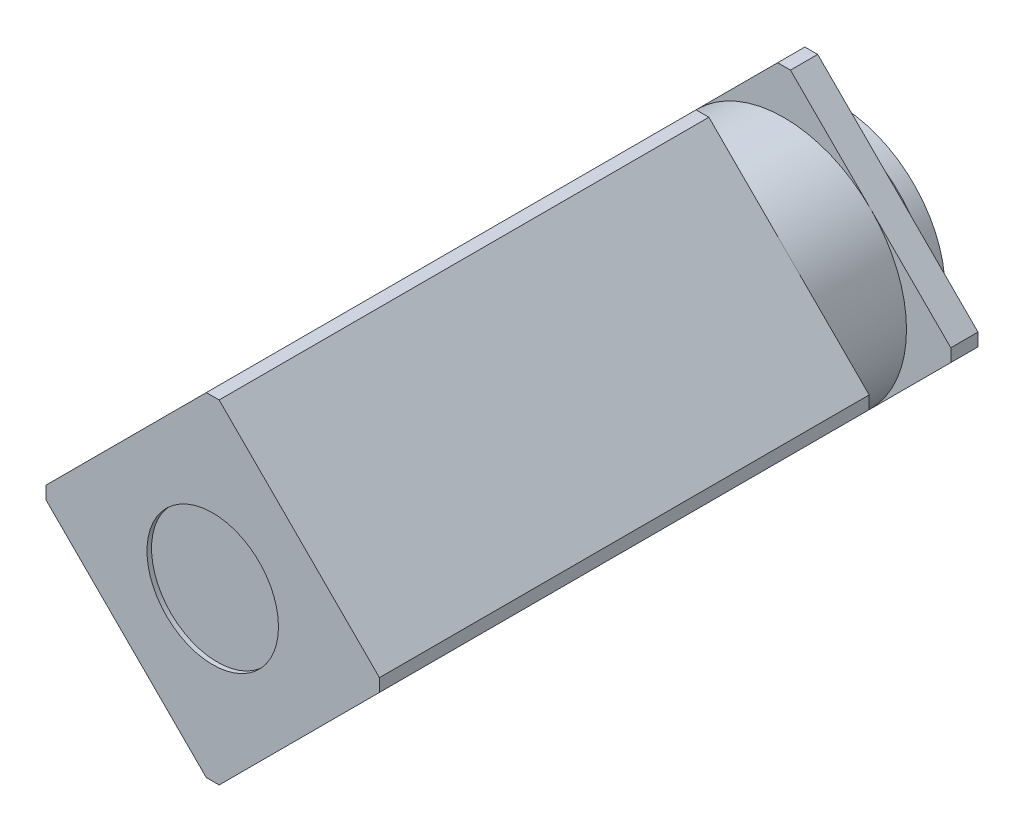
SolidWorks part; units mm, degrees
ref_plane "정면" through (0, 0, 0) normal (0, 0, 1) x (1, 0, 0)
ref_plane "윗면" through (0, 0, 0) normal (0, 1, 0) x (1, 0, 0)
ref_plane "우측면" through (0, 0, 0) normal (1, 0, 0) x (0, 0, -1)
sketch "스케치1" plane through (0, 0, 0) normal (0, 0, 1) x (1, 0, 0)
  line L0 (-6.7696, 334.4142) -> (-6.7696, 331.5858)
  line L1 (-6.7696, 331.5858) -> (28.5858, 296.2304)
  line L2 (28.5858, 296.2304) -> (31.4142, 296.2304)
  line L3 (31.4142, 296.2304) -> (66.7696, 331.5858)
  line L4 (66.7696, 331.5858) -> (66.7696, 334.4142)
  line L5 (66.7696, 334.4142) -> (31.4142, 369.7696)
  line L6 (31.4142, 369.7696) -> (28.5858, 369.7696)
  line L7 (28.5858, 369.7696) -> (-6.7696, 334.4142)
extrude "보스-돌출1" add sketch "스케치1" against normal blind 108
sketch "스케치2" plane through (0, 0, -108) normal (0, 0, -1) x (-1, 0, 0)
  circle A0 centre (-30, 333) radius 27
extrude "보스-돌출2" add sketch "스케치2" along normal blind 18
sketch "스케치3" plane through (0, 0, -126) normal (0, 0, -1) x (-1, 0, 0)
  line L0 (6.7696, 331.5858) -> (6.7696, 334.4142)
  line L1 (6.7696, 334.4142) -> (-28.5858, 369.7696)
  line L2 (-28.5858, 369.7696) -> (-31.4142, 369.7696)
  line L3 (-31.4142, 369.7696) -> (-66.7696, 334.4142)
  line L4 (-31.4142, 369.7696) -> (-66.7696, 334.4142) construction
  line L5 (-66.7696, 334.4142) -> (-66.7696, 331.5858)
  line L6 (-66.7696, 331.5858) -> (-31.4142, 296.2304)
  line L7 (-31.4142, 296.2304) -> (-28.5858, 296.2304)
  line L8 (-28.5858, 296.2304) -> (6.7696, 331.5858)
extrude "보스-돌출3" add sketch "스케치3" along normal blind 6
sketch "스케치4" plane through (0, 0, -132) normal (0, 0, -1) x (-1, 0, 0)
  circle A0 centre (-30, 333) radius 24.5
extrude "보스-돌출4" add sketch "스케치4" along normal blind 2
sketch "스케치5" plane through (0, 0, -134) normal (0, 0, -1) x (-1, 0, 0)
  circle A0 centre (-30, 333) radius 23.5
extrude "보스-돌출5" add sketch "스케치5" along normal blind 4
sketch "스케치7" plane through (-132.4081, 132.4081, 0) normal (0.7071, -0.7071, 0) x (0, 0, -1)
  circle A0 centre (105, 274.6798) radius 1.6
  circle A1 centre (93, 274.6798) radius 1.45
  circle A2 centre (81, 274.6798) radius 1.45
  circle A3 centre (69, 274.6798) radius 1.45
  circle A4 centre (57, 274.6798) radius 1.45
  circle A5 centre (45, 274.6798) radius 1.45
  circle A6 centre (33, 274.6798) radius 1.45
  circle A7 centre (21, 274.6798) radius 1.4645
  circle A8 centre (21, 238.6798) radius 1.45
  circle A9 centre (33, 238.6798) radius 1.45
  circle A10 centre (45, 238.6798) radius 1.45
  circle A11 centre (57, 238.6798) radius 1.45
  circle A12 centre (69, 238.6798) radius 1.45
  circle A13 centre (81, 238.6798) radius 1.45
  circle A14 centre (93, 238.6798) radius 1.45
  circle A15 centre (105, 238.6798) radius 1.6
extrude "컷-돌출1" cut sketch "스케치7" against normal blind 14
sketch "스케치8" plane through (0, 0, 0) normal (0, 0, 1) x (1, 0, 0)
  circle A0 centre (30, 333) radius 14.5
extrude "컷-돌출2" cut sketch "스케치8" against normal blind 1
